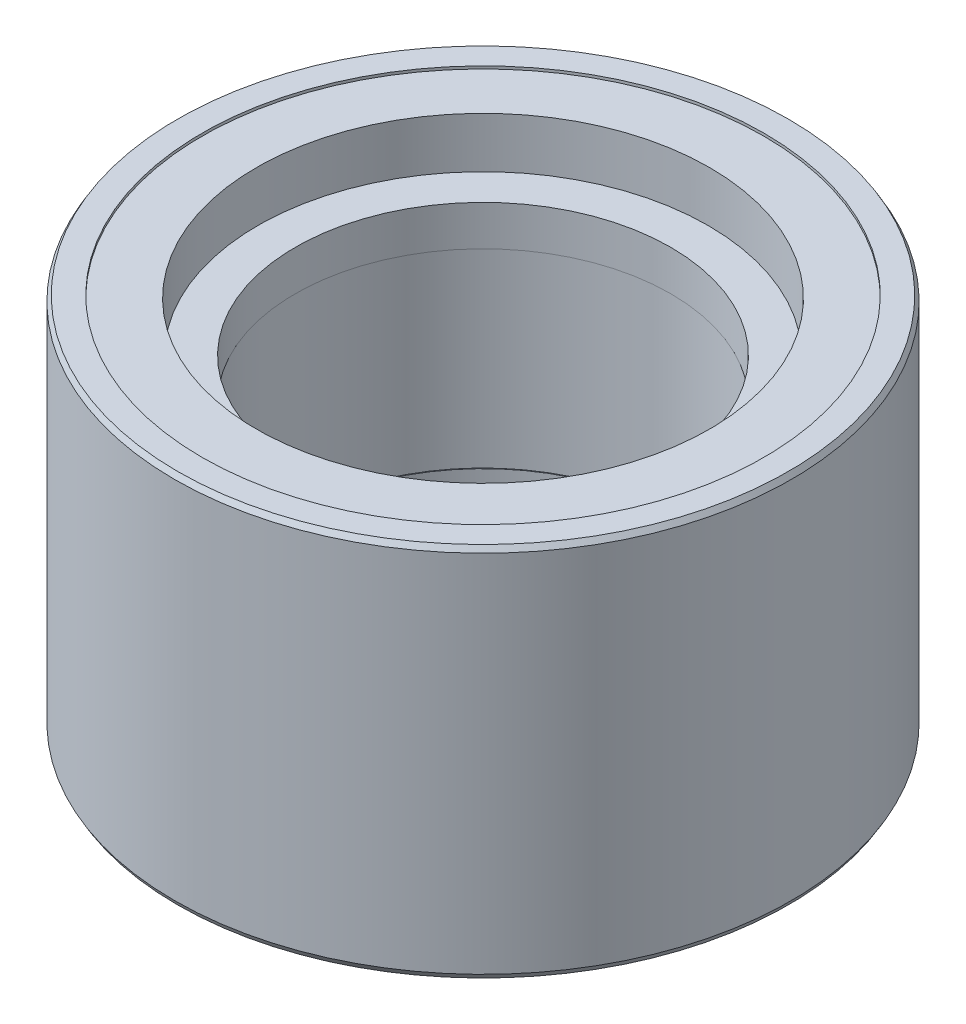
SolidWorks part; units mm, degrees
ref_plane "前基準面" through (0, 0, 0) normal (0, 0, 1) x (1, 0, 0)
ref_plane "上基準面" through (0, 0, 0) normal (0, 1, 0) x (1, 0, 0)
ref_plane "右基準面" through (0, 0, 0) normal (1, 0, 0) x (0, 0, -1)
sketch "草圖1" plane through (0, 0, 0) normal (0, 0, 1) x (1, 0, 0)
  line L0 (70, 120.5) -> (70, 105.5)
  line L1 (70, 105.5) -> (70.3, 105.5)
  line L2 (70.3, 105.5) -> (70.3, 34.5)
  line L3 (70.3, 34.5) -> (70, 34.5)
  line L4 (70, 34.5) -> (70, 19.5)
  line L5 (70, 19.5) -> (84, 19.5)
  line L6 (84, 19.5) -> (84, 120.5)
  line L7 (84, 120.5) -> (70, 120.5)
  line L8 (0, 120.5) -> (0, 19.5) construction
revolve "旋轉1" add sketch "草圖1" angle 360 about L8
sketch "草圖2" plane through (0, 0, 0) normal (0, 0, 1) x (1, 0, 0)
  line L0 (84.5, 1) -> (104.75, 1)
  line L1 (104.75, 1) -> (104.75, 0)
  line L2 (104.75, 0) -> (115, 0)
  line L4 (104.75, 139) -> (104.75, 140)
  line L5 (84.5, 1) -> (84.5, 139)
  line L6 (84.5, 139) -> (104.75, 139)
  line L10 (115, 138) -> (115, 0)
  line L11 (104.75, 140) -> (113.8453, 140)
  line L12 (113.8453, 140) -> (115, 138)
  line L13 (113.8453, 0) -> (115, 2)
  line L14 (0, 0) -> (0, 306.7432) construction
  dimension "D1" = 84.5
  dimension "D2" = 1
  dimension "D3" = 1
  dimension "D4" = 104.75
  dimension "D5" = 115
  dimension "D6" = 30
  dimension "D7" = 2
  dimension "D8" = 2
  dimension "D9" = 60
  dimension "D10" = 139
  dimension "D11" = 104.75
  dimension "D12" = 1
revolve "旋轉2" add sketch "草圖2" angle 360 about L14
